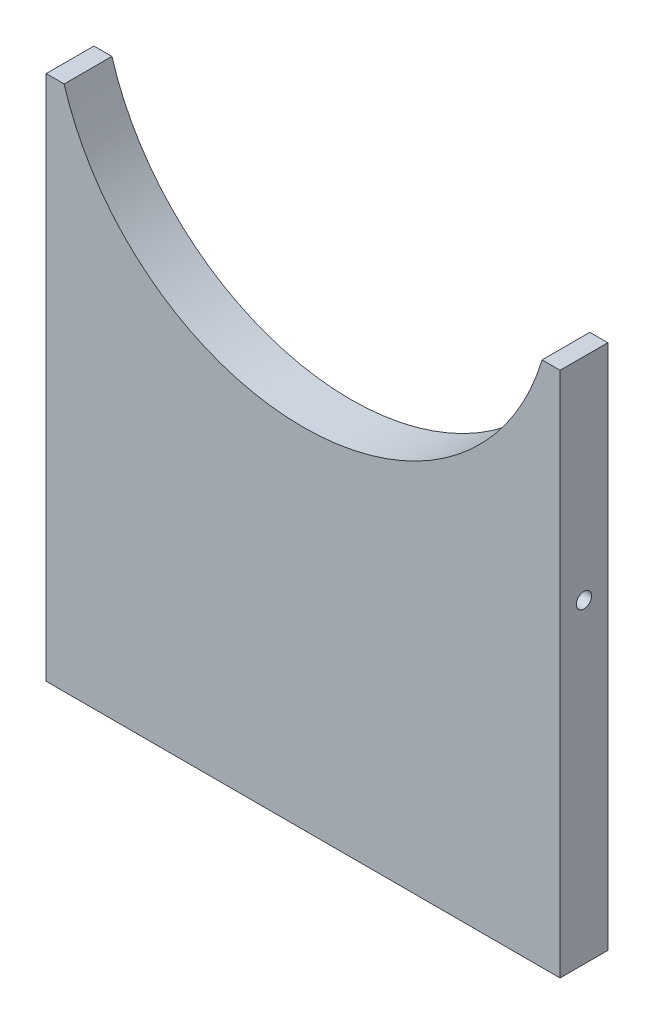
SolidWorks part; units mm, degrees
material "6061 Alloy"
ref_plane "Front Plane" through (0, 0, 0) normal (0, 0, 1) x (1, 0, 0)
ref_plane "Top Plane" through (0, 0, 0) normal (0, 1, 0) x (1, 0, 0)
ref_plane "Right Plane" through (0, 0, 0) normal (1, 0, 0) x (0, 0, -1)
sketch "Sketch1" plane through (0, 0, 0) normal (0, 0, 1) x (1, 0, 0)
  line L0 (0, 0) -> (0, 140)
  line L1 (0, 140) -> (4.7864, 140)
  line L2 (0, 0) -> (136.7, 0)
  line L3 (136.7, 0) -> (136.7, 140)
  line L4 (131.9136, 140) -> (136.7, 140)
  line L5 (68.35, 149.9518) -> (68.35, 159.0958) construction
  arc A0 (4.7864, 140) -> (131.9136, 140) centre (68.35, 159.0958) ccw
  dimension "D1" = 140
  dimension "D2" = 140
  dimension "D3" = 136.7
  dimension "D4" = 9.144
extrude "Boss-Extrude1" add sketch "Sketch1" along normal blind 12.7
sketch "Sketch2" plane through (136.7, 0, 0) normal (1, 0, 0) x (0, 0, -1)
  line L0 (-6.35, 140) -> (-6.35, 83.866) construction
  dimension "D1" = 56.134
hole_wizard "#10-32 Tapped Hole1" positions "3DSketch1" profile "Sketch3" tap size "#10-32" standard "Ansi Inch"
sketch3d "3DSketch1"
  point P0 (136.7, 83.866, 6.35)
sketch "Sketch3" plane through (136.7, 83.866, 6.35) normal (0, 1, 0) x (0, 0, -1)
  line L0 (0, 0) -> (0, 26.6133)
  line L1 (0, 26.6133) -> (2.0193, 25.4)
  line L2 (2.0193, 25.4) -> (2.0193, 0)
  line L5 (2.0193, 0) -> (0, 0)
  line L10 (0, 26.6133) -> (-2.0193, 25.4) construction
  line L11 (0, -6.35) -> (0, 107.95) construction
  dimension "Tap Drill Dia." = 4.0386
  dimension "Tap Drill Depth" = 25.4
  dimension "Drill Angle" = 118
sketch "Sketch4" plane through (0, 0, 0) normal (0, 0, 1) x (1, 0, 0)
  line L0 (68.35, 83.5518) -> (68.35, 0) construction
  line L1 (0, 0) -> (136.7, 0) construction
  line L2 (68.35, 83.5518) -> (68.35, 0) construction
sketch "Sketch5" plane through (0, 0, 12.7) normal (0, 0, 1) x (1, 0, 0)
  line L0 (68.35, 83.5518) -> (68.35, 0) construction
ref_plane "Plane1" through (68.35, 0, 0) normal (1, 0, 0) x (0, 0, -1)
mirror "Mirror3" about plane through (68.35, 0, 0) normal (1, 0, 0) of "#10-32 Tapped Hole1"
sketch "Sketch6" plane through (0, 0, 0) normal (0, -1, 0) x (1, 0, 0)
  line L0 (0, 6.35) -> (24.35, 6.35) construction
  line L1 (0, 12.7) -> (0, 0) construction
  line L2 (24.35, 6.35) -> (112.35, 6.35) construction
  line L6 (112.35, 6.35) -> (136.7, 6.35) construction
  line L7 (136.7, 12.7) -> (136.7, 0) construction
  dimension "D1" = 88
  dimension "D2" = 24.35
  dimension "D3" = 24.35
hole_wizard "#10-32 Tapped Hole2" positions "3DSketch2" profile "Sketch7" tap size "#10-32" standard "Ansi Inch"
sketch3d "3DSketch2"
  point P0 (112.35, 0, 6.35)
  point P3 (24.35, 0, 6.35)
sketch "Sketch7" plane through (112.35, 0, 6.35) normal (1, 0, 0) x (0, 0, -1)
  line L0 (0, 0) -> (0, 26.6133)
  line L1 (0, 26.6133) -> (2.0193, 25.4)
  line L2 (2.0193, 25.4) -> (2.0193, 0)
  line L5 (2.0193, 0) -> (0, 0)
  line L10 (0, 26.6133) -> (-2.0193, 25.4) construction
  line L11 (0, -6.35) -> (0, 107.95) construction
  dimension "Tap Drill Dia." = 4.0386
  dimension "Tap Drill Depth" = 25.4
  dimension "Drill Angle" = 118
